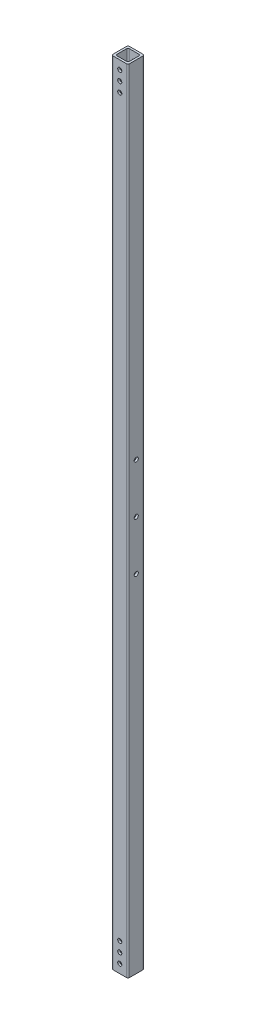
SolidWorks part; units mm, degrees
material "6061-T6 (SS)"
ref_plane "Front Plane" through (0, 0, 0) normal (0, 0, 1) x (1, 0, 0)
ref_plane "Top Plane" through (0, 0, 0) normal (0, 1, 0) x (1, 0, 0)
ref_plane "Right Plane" through (0, 0, 0) normal (1, 0, 0) x (0, 0, -1)
sketch "Sketch1" plane through (0, 0, 0) normal (0, 1, 0) x (1, 0, 0)
  line L0 (9.525, 9.525) -> (-9.525, 9.525)
  line L1 (12.7, -12.7) -> (-12.7, -12.7)
  line L2 (12.7, -12.7) -> (12.7, 12.7)
  line L3 (12.7, 12.7) -> (-12.7, 12.7)
  line L4 (-12.7, -12.7) -> (-12.7, 12.7)
  line L5 (12.7, -12.7) -> (-12.7, 12.7) construction
  line L6 (12.7, 12.7) -> (-12.7, -12.7) construction
  line L7 (-9.525, -9.525) -> (-9.525, 9.525)
  line L8 (9.525, -9.525) -> (-9.525, -9.525)
  line L9 (9.525, -9.525) -> (9.525, 9.525)
  point P0 (0, 0)
  dimension "D1" = 25.4
  dimension "D2" = 25.4
  dimension "D3" = 3.175
extrude "Boss-Extrude1" add sketch "Sketch1" along normal mid plane 1219.2
fillet "Fillet1" radius 2.1082 8 edges at (9.525, 0, -9.525) (-9.525, 0, -9.525) (-9.525, 0, 9.525) (9.525, 0, 9.525) (12.7, 0, -12.7) (-12.7, 0, -12.7) (-12.7, 0, 12.7) (12.7, 0, 12.7)
sketch "Sketch6" plane through (0, 0, -12.7) normal (0, 0, -1) x (-1, 0, 0)
  line L0 (0, 609.6) -> (0, 600.8737) construction
  line L2 (0, 402.295) -> (0, -606.425) construction
  line L3 (-10.5918, 609.6) -> (10.5918, 609.6) construction
  line L7 (0, 0) -> (10.5918, 0) construction
  line L8 (10.5918, -609.6) -> (10.5918, 609.6) construction
  line L9 (0, 609.6) -> (0, 558.8) construction
  circle A12 centre (0, 565.785) radius 3.175
  circle A13 centre (0, 581.025) radius 3.175
  circle A14 centre (0, 596.265) radius 3.175
  point P29 (0, 565.785)
  point P31 (0, 581.025)
  point P32 (0, 596.265)
  dimension "D1" = 15.24
  dimension "D2" = 15.24
  dimension "D3" = 13.335
  dimension "D7" = 50.8
extrude "Cut-Extrude5" cut sketch "Sketch6" against normal through all
sketch "Sketch7" plane through (-12.7, 0, 0) normal (-1, 0, 0) x (0, 0, 1)
  circle A0 centre (0, 0) radius 3.175
  dimension "D1" = 6.35
extrude "Cut-Extrude6" cut sketch "Sketch7" against normal through all
sketch "Sketch8" plane through (-12.7, 0, 0) normal (-1, 0, 0) x (0, 0, 1)
  line L0 (0, 0) -> (0, -76.2) construction
  circle A0 centre (0, -76.2) radius 3.175
  dimension "D2" = 6.35
  dimension "D1" = 76.2
extrude "Cut-Extrude7" cut sketch "Sketch8" against normal through all
mirror "Mirror1" about plane through (0, 0, 0) normal (0, 1, 0) of "Cut-Extrude7"
mirror "Mirror2" about plane through (0, 0, 0) normal (0, 1, 0) of "Cut-Extrude5"
